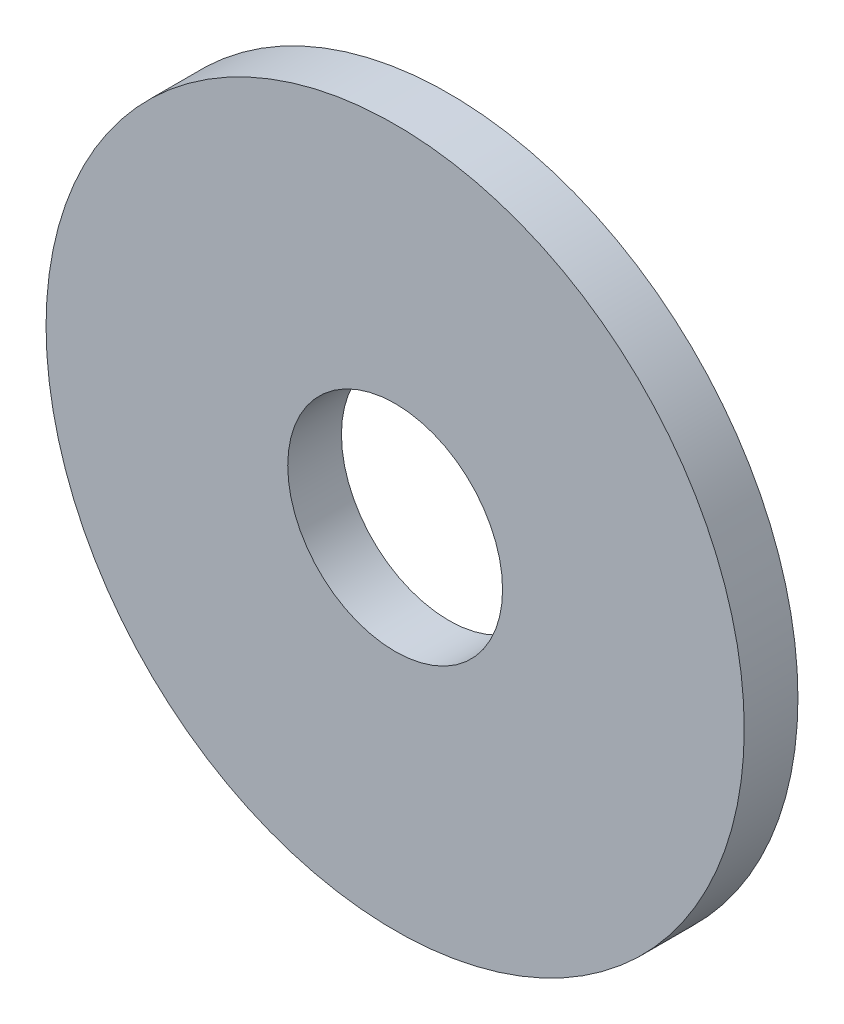
SolidWorks part; units mm, degrees
material "铸造合金钢"
ref_plane "Front" through (0, 0, 0) normal (0, 0, 1) x (1, 0, 0)
ref_plane "Top" through (0, 0, 0) normal (0, 1, 0) x (1, 0, 0)
ref_plane "Right" through (0, 0, 0) normal (1, 0, 0) x (0, 0, -1)
sketch "草图1" plane through (0, 0, 0) normal (0, 0, 1) x (1, 0, 0)
  circle A0 centre (0, 0) radius 1
  circle A1 centre (0, 0) radius 3.25
extrude "凸台-拉伸1" add sketch "草图1" along normal blind 0.5
